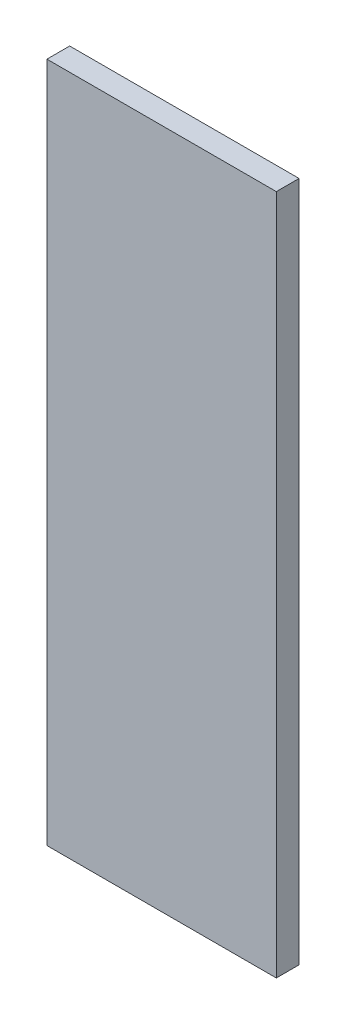
SolidWorks part; units mm, degrees
ref_plane "Plan de face" through (0, 0, 0) normal (0, 0, 1) x (1, 0, 0)
ref_plane "Plan de dessus" through (0, 0, 0) normal (0, 1, 0) x (1, 0, 0)
ref_plane "Plan de droite" through (0, 0, 0) normal (1, 0, 0) x (0, 0, -1)
sketch "Esquisse1" plane through (0, 0, 0) normal (0, 0, 1) x (1, 0, 0)
  line L1 (-20.2753, 24.1391) -> (-4.2753, 24.1391)
  line L2 (-20.2753, 24.1391) -> (-20.2753, -23.3609)
  line L3 (-20.2753, -23.3609) -> (-4.2753, -23.3609)
  line L4 (-4.2753, 24.1391) -> (-4.2753, -23.3609)
  dimension "D1" = 16
  dimension "D2" = 47.5
extrude "Boss.-Extru.1" add sketch "Esquisse1" along normal blind 1.5875
